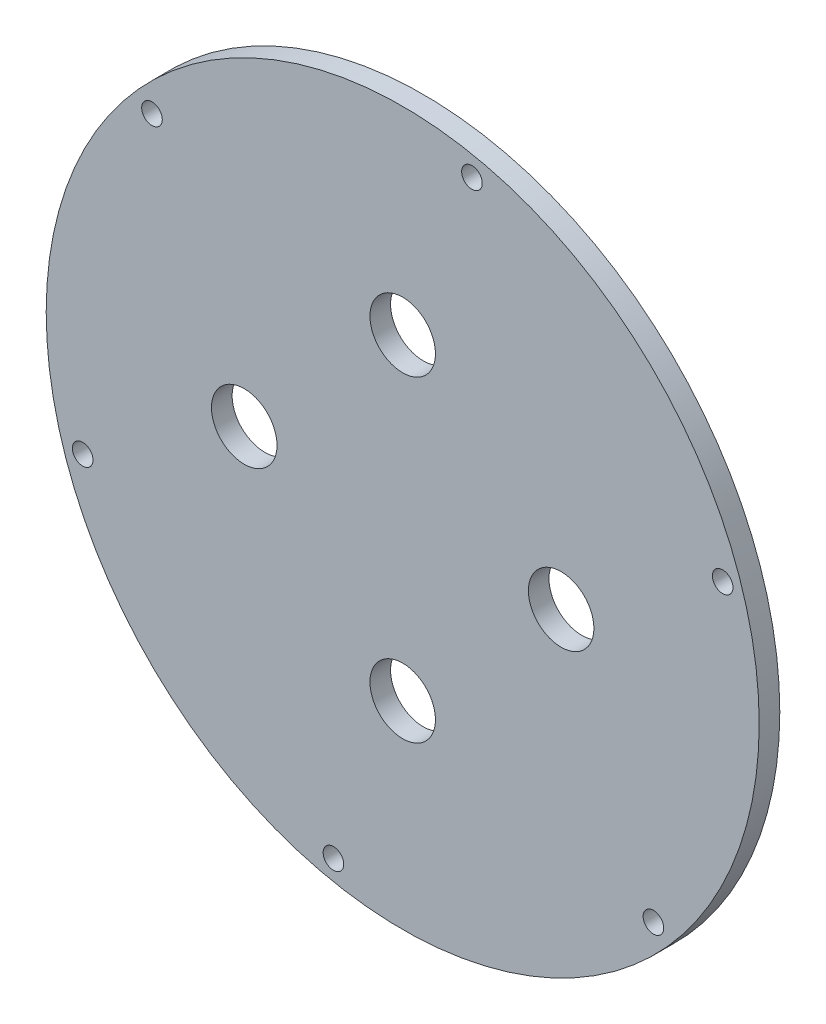
SolidWorks part; units mm, degrees
ref_plane "前视基准面" through (0, 0, 0) normal (0, 0, 1) x (1, 0, 0)
ref_plane "上视基准面" through (0, 0, 0) normal (0, 1, 0) x (1, 0, 0)
ref_plane "右视基准面" through (0, 0, 0) normal (1, 0, 0) x (0, 0, -1)
sketch "草图1" plane through (0, 0, 0) normal (0, 0, 1) x (1, 0, 0)
  circle A0 centre (0, 0) radius 57.15
  dimension "D1" = 114.3
extrude "凸台-拉伸1" add sketch "草图1" along normal blind 3.302
sketch "草图2" plane through (0, 0, 0) normal (0, 0, -1) x (-1, 0, 0)
  circle A0 centre (-51.2954, 16.7952) radius 1.651
  circle A1 centre (-11.1026, 52.8208) radius 1.651
  circle A2 centre (40.1928, 36.0255) radius 1.651
  circle A3 centre (51.2954, -16.7952) radius 1.651
  circle A5 centre (11.1026, -52.8208) radius 1.651
  circle A6 centre (-40.1928, -36.0255) radius 1.651
  point P15 (0, 0)
  dimension "D1" = 3.302
extrude "切除-拉伸1" cut sketch "草图2" against normal through all
hole_wizard "M10 Clearance Hole1" positions "Sketch2" profile "Sketch3" hole size "M10" standard "ANSI Metric"
sketch "Sketch2" plane through (0, 0, 0) normal (0, 0, -1) x (-1, 0, 0)
  point P0 (-25.4, 0)
  point P2 (25.4, 0)
  point P6 (0, 0)
  dimension "D1" = 25.4
  dimension "D2" = 25.4
sketch "Sketch3" plane through (25.4, 0, 0) normal (1, 0, 0) x (0, 1, 0)
  line L0 (0, 0) -> (0, 28.5545)
  line L1 (0, 28.5545) -> (5.25, 25.4)
  line L2 (5.25, 25.4) -> (5.25, 0)
  line L5 (5.25, 0) -> (0, 0)
  line L10 (0, 28.5545) -> (-5.25, 25.4) construction
  line L11 (0, -6.35) -> (0, 107.95) construction
  dimension "Hole Dia." = 10.5
  dimension "Hole Depth" = 25.4
  dimension "Drill Angle" = 118
pattern_circular "CirPattern1" count 4 over 360 about axis through (0, 0, 0) along (0, 0, 1) of "M10 Clearance Hole1"
